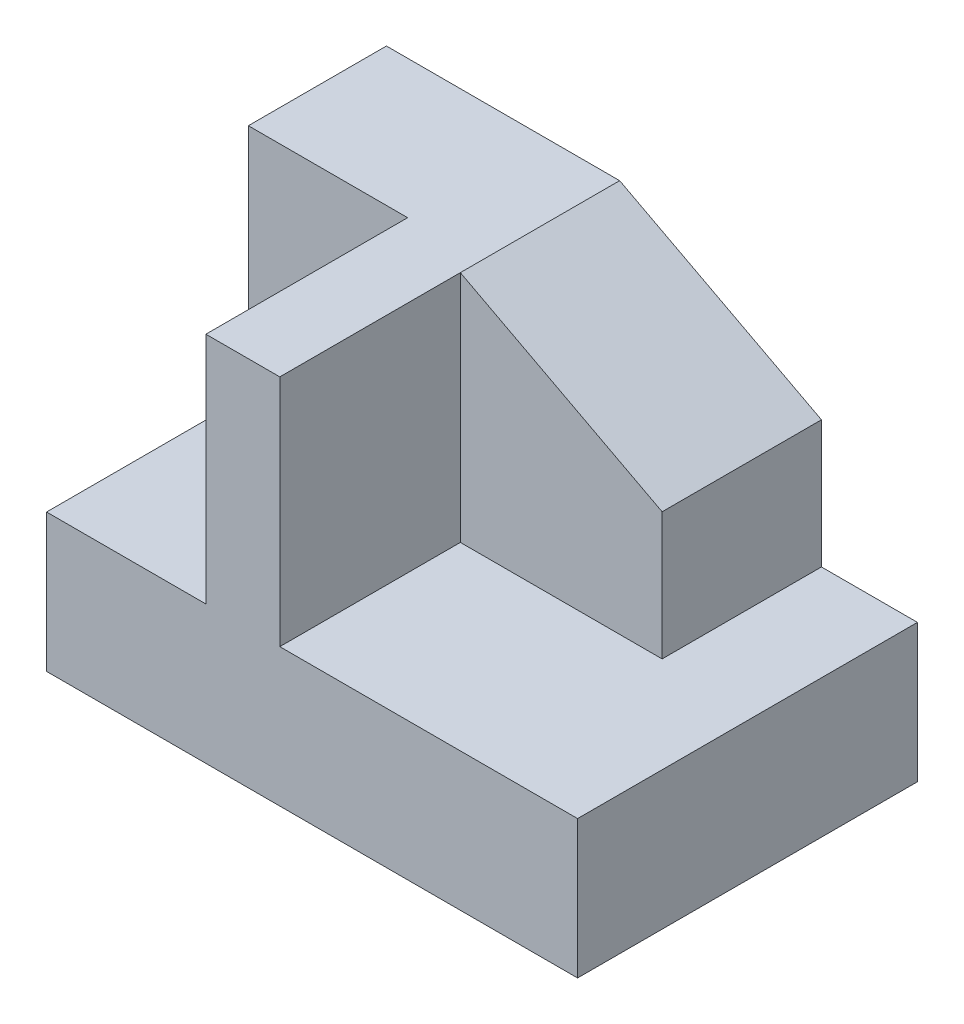
SolidWorks part; units mm, degrees
ref_plane "Front Plane" through (0, 0, 0) normal (0, 0, 1) x (1, 0, 0)
ref_plane "Top Plane" through (0, 0, 0) normal (0, 1, 0) x (1, 0, 0)
ref_plane "Right Plane" through (0, 0, 0) normal (1, 0, 0) x (0, 0, -1)
sketch "Sketch1" plane through (0, 0, 0) normal (0, 1, 0) x (1, 0, 0)
  line L1 (-25, -16) -> (25, -16)
  line L2 (-25, -16) -> (-25, 16)
  line L3 (-25, 16) -> (25, 16)
  line L4 (25, -16) -> (25, 16)
  line L5 (-25, -16) -> (25, 16) construction
  line L6 (-25, 16) -> (25, -16) construction
  point P0 (0, 0)
  dimension "D1" = 50
  dimension "D2" = 32
extrude "Boss-Extrude1" add sketch "Sketch1" along normal blind 13
sketch "Sketch2" plane through (0, 0, -16) normal (0, 0, -1) x (-1, 0, 0)
  line L1 (25, 13) -> (10, 13)
  line L2 (25, 13) -> (25, 35)
  line L3 (25, 35) -> (10, 35)
  line L4 (10, 13) -> (10, 35)
  dimension "D1" = 15
  dimension "D2" = 22
extrude "Boss-Extrude2" add sketch "Sketch2" against normal blind 13
sketch "Sketch3" plane through (0, 0, 16) normal (0, 0, 1) x (1, 0, 0)
  line L1 (-10, 13) -> (-3.0386, 13)
  line L2 (-10, 13) -> (-10, 35)
  line L3 (-10, 35) -> (-3.0386, 35)
  line L4 (-3.0386, 13) -> (-3.0386, 35)
extrude "Boss-Extrude3" add sketch "Sketch3" against normal blind 32
sketch "Sketch4" plane through (0, 0, -16) normal (0, 0, -1) x (-1, 0, 0)
  line L1 (3.0386, 13) -> (-15.9614, 13)
  line L2 (3.0386, 13) -> (3.0386, 25)
  line L3 (3.0386, 25) -> (-15.9614, 25)
  line L4 (-15.9614, 13) -> (-15.9614, 25)
extrude "Boss-Extrude4" add sketch "Sketch4" against normal blind 15
sketch "Sketch5" plane through (0, 0, -16) normal (0, 0, -1) x (-1, 0, 0)
  line L0 (-15.9614, 25) -> (3.0386, 35)
  line L1 (3.0386, 35) -> (3.0386, 25)
  line L2 (3.0386, 25) -> (-15.9614, 25)
extrude "Boss-Extrude5" add sketch "Sketch5" against normal blind 15
